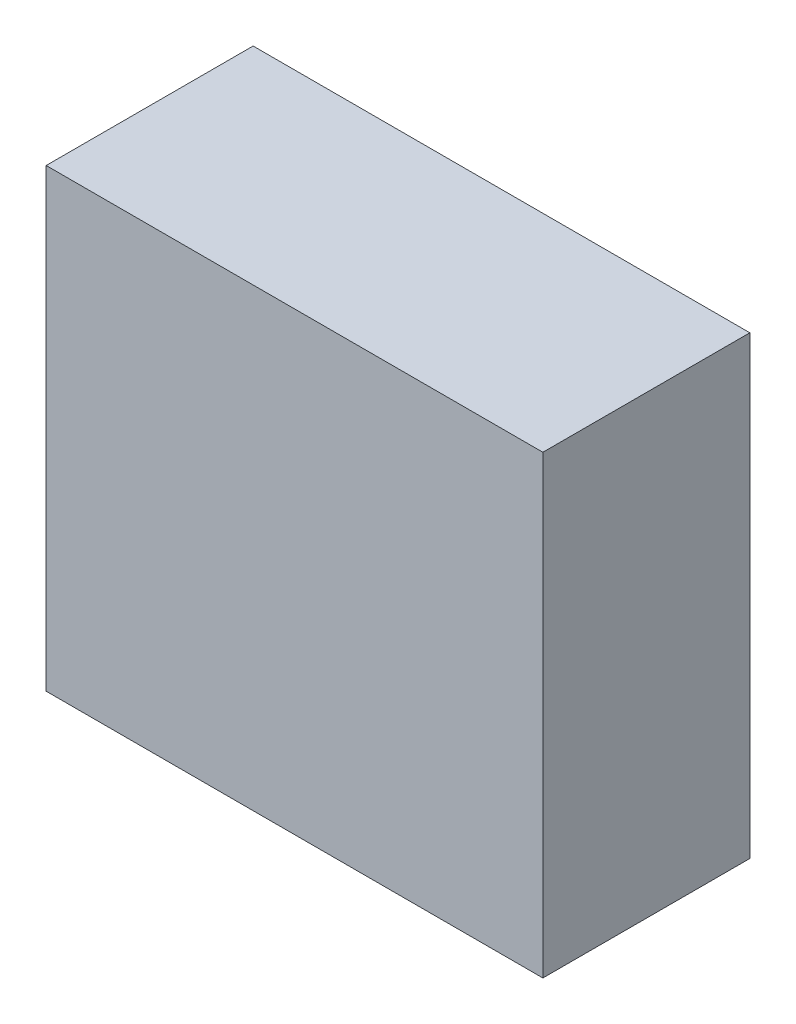
SolidWorks part; units mm, degrees
ref_plane "Front Plane" through (0, 0, 0) normal (0, 0, 1) x (1, 0, 0)
ref_plane "Top Plane" through (0, 0, 0) normal (0, 1, 0) x (1, 0, 0)
ref_plane "Right Plane" through (0, 0, 0) normal (1, 0, 0) x (0, 0, -1)
other "Configuration Table"
sketch "Sketch1" plane through (0, 0, 0) normal (0, 0, 1) x (1, 0, 0)
  line L1 (850, 1690) -> (970, 1690)
  line L2 (850, 1690) -> (850, 1800)
  line L3 (850, 1800) -> (970, 1800)
  line L4 (970, 1690) -> (970, 1800)
extrude "STORE_pano_PLC_ModbusTCP_1" add sketch "Sketch1" against normal blind 50 from offset 650 separate body
